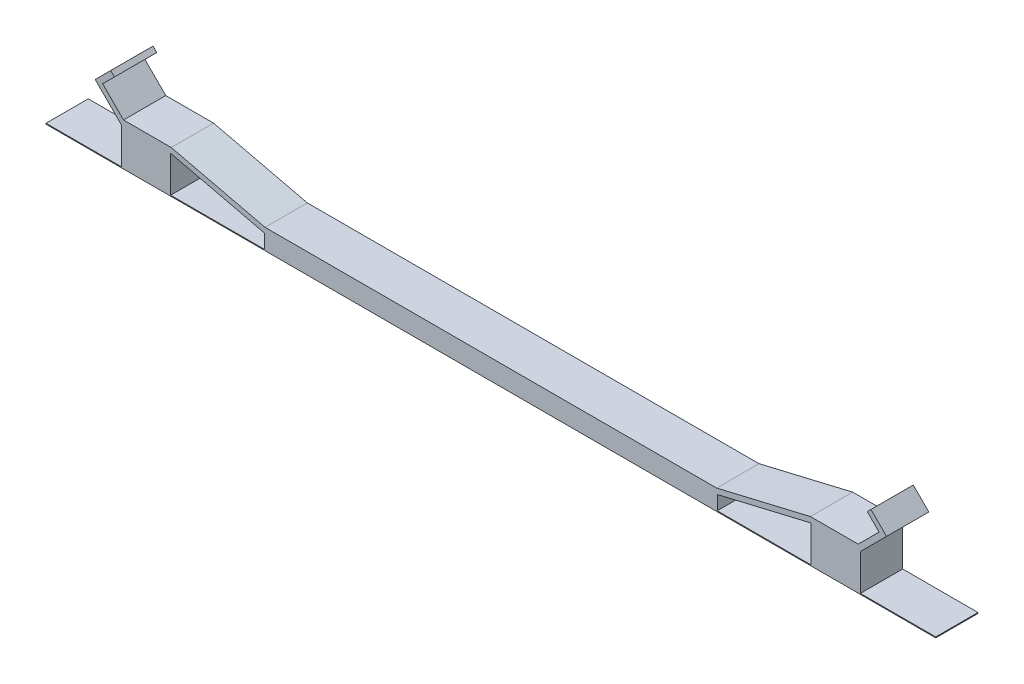
SolidWorks part; units mm, degrees
ref_plane "Front Plane" through (0, 0, 0) normal (0, 0, 1) x (1, 0, 0)
ref_plane "Top Plane" through (0, 0, 0) normal (0, 1, 0) x (1, 0, 0)
ref_plane "Right Plane" through (0, 0, 0) normal (1, 0, 0) x (0, 0, -1)
sketch "Sketch2" plane through (0, 0, 0) normal (0, 1, 0) x (1, 0, 0)
  line L1 (505, -24) -> (-505, -24)
  line L2 (505, -24) -> (505, 24)
  line L3 (505, 24) -> (-505, 24)
  line L4 (-505, -24) -> (-505, 24)
  line L5 (505, -24) -> (-505, 24) construction
  line L6 (505, 24) -> (-505, -24) construction
  point P0 (0, 0)
  dimension "D1" = 1010
  dimension "D2" = 48
extrude "Boss-Extrude1" add sketch "Sketch2" along normal blind 1
sketch "Sketch3" plane through (0, 1, 0) normal (0, 1, 0) x (1, 0, 0)
  line L1 (257, -24) -> (-257, -24)
  line L2 (257, -24) -> (257, 24)
  line L3 (257, 24) -> (-257, 24)
  line L4 (-257, -24) -> (-257, 24)
  line L5 (257, -24) -> (-257, 24) construction
  line L6 (257, 24) -> (-257, -24) construction
  point P0 (0, 0)
  dimension "D1" = 514
  dimension "D2" = 48
extrude "Boss-Extrude2" add sketch "Sketch3" along normal blind 16
sketch "Sketch4" plane through (0, 1, 0) normal (0, 1, 0) x (1, 0, 0)
  line L0 (-505, -24) -> (-257, -24) construction
  line L1 (-363.4949, -24) -> (-419.4949, -24)
  line L2 (-363.4949, -24) -> (-363.4949, 24)
  line L3 (-363.4949, 24) -> (-419.4949, 24)
  line L4 (-419.4949, -24) -> (-419.4949, 24)
  line L5 (-257, 24) -> (-505, 24) construction
  dimension "D1" = 56
extrude "Boss-Extrude3" add sketch "Sketch4" along normal blind 41.2
mirror "Mirror1" about plane through (0, 0, 0) normal (1, 0, 0) of "Boss-Extrude1", "Boss-Extrude3"
sketch "Sketch7" plane through (0, 0, 24) normal (0, 0, 1) x (1, 0, 0)
  line L0 (-419.4949, 42.2) -> (-363.4949, 42.2)
  line L1 (-363.4949, 42.2) -> (-257, 17)
  line L2 (-257, 17) -> (257, 17)
  line L3 (257, 17) -> (363.4949, 42.2)
  line L4 (363.4949, 42.2) -> (419.4949, 42.2)
  line L5 (419.4949, 42.2) -> (449.1934, 71.8985)
  line L6 (449.1934, 71.8985) -> (431.5157, 89.5762)
  line L7 (-419.4949, 42.2) -> (-449.1934, 71.8985)
  line L8 (-449.1934, 71.8985) -> (-431.5157, 89.5762)
  dimension "D1" = 42
  dimension "D2" = 25
  dimension "D3" = 42
  dimension "D4" = 25
  dimension "D5" = 90
extrude "Extrude-Thin1" add sketch "Sketch7" against normal blind 48 thin thin type one direction wall 6
